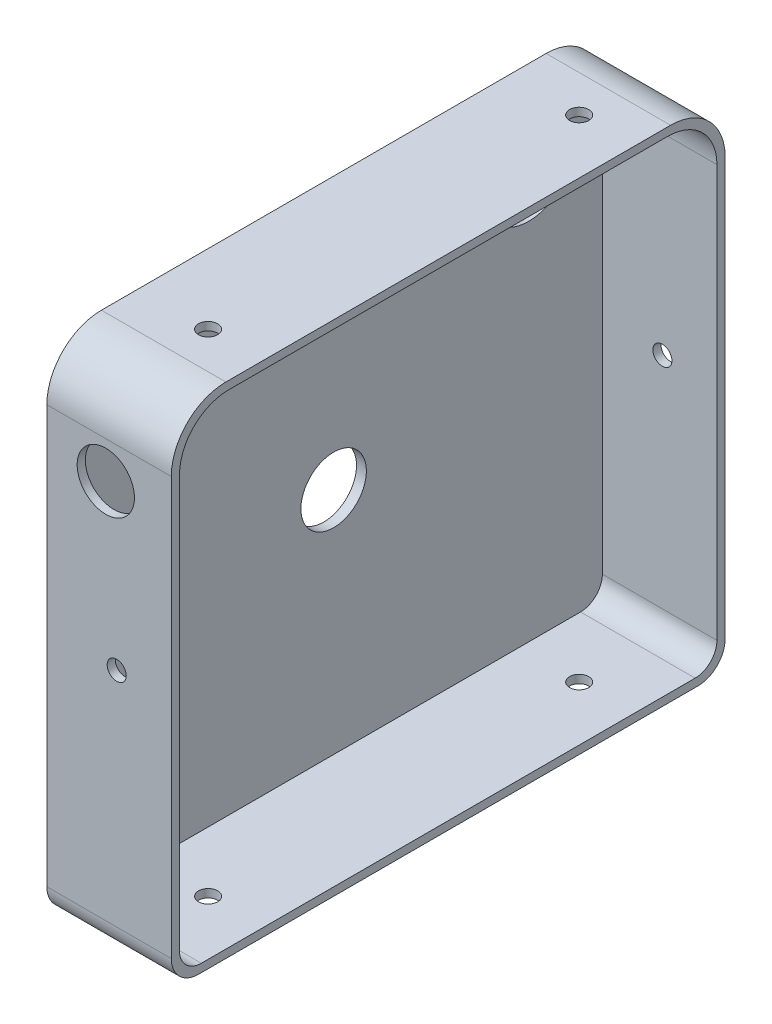
SolidWorks part; units mm, degrees
ref_plane "前视基准面" through (0, 0, 0) normal (0, 0, 1) x (1, 0, 0)
ref_plane "上视基准面" through (0, 0, 0) normal (0, 1, 0) x (1, 0, 0)
ref_plane "右视基准面" through (0, 0, 0) normal (1, 0, 0) x (0, 0, -1)
sketch "草图1" plane through (0, 0, 0) normal (1, 0, 0) x (0, 0, -1)
  line L0 (1.5, 1.5) -> (1.5, 90)
  line L1 (0, 0) -> (101.5, 0)
  line L2 (0, 0) -> (0, 91.5)
  line L3 (0, 91.5) -> (101.5, 91.5)
  line L4 (101.5, 0) -> (101.5, 91.5)
  line L5 (1.5, 90) -> (100, 90)
  line L6 (100, 1.5) -> (100, 90)
  line L7 (1.5, 1.5) -> (100, 1.5)
  dimension "D1" = 101.5
  dimension "D2" = 91.5
  dimension "D3" = 1.5
extrude "凸台-拉伸1" add sketch "草图1" along normal blind 21
sketch "草图2" plane through (0, 0, 0) normal (-1, 0, 0) x (0, 0, 1)
  line L0 (-50.75, 90) -> (-50.75, -4.3889) construction
  line L1 (-101.5, 91.5) -> (0, 91.5)
  line L2 (-101.5, 91.5) -> (-101.5, 0)
  line L3 (-101.5, 0) -> (0, 0)
  line L4 (0, 91.5) -> (0, 0)
  line L5 (-100, 90) -> (-1.5, 90) construction
  line L6 (-1.5, 1.5) -> (-100, 1.5) construction
  circle A0 centre (-86.5, 76.5) radius 8.25
  circle A1 centre (-50.75, 43.5) radius 6
  dimension "D1" = 12
  dimension "D2" = 16.5
  dimension "D5" = 42
  dimension "D3" = 15
  dimension "D4" = 15
extrude "凸台-拉伸2" add sketch "草图2" along normal blind 1.8
sketch "草图3" plane through (0, 0, 0) normal (0, 0, 1) x (1, 0, 0)
  line L0 (11, 95.0538) -> (11, -6.5657) construction
  line L3 (-1.8, 45.75) -> (35.7467, 45.75) construction
  line L4 (-1.8, 0) -> (-1.8, 91.5) construction
  line L5 (21, 91.5) -> (21, 0) construction
  circle A1 centre (11, 45.75) radius 1.75
  point P8 (12.2397, 46)
  point P11 (10, 46)
  dimension "D1" = 10
  dimension "D2" = 3.5
extrude "切除-拉伸1" cut sketch "草图3" against normal through all
sketch "草图4" plane through (0, 91.5, 0) normal (0, 1, 0) x (1, 0, 0)
  line L0 (11, 109.1455) -> (11, -1.1086) construction
  line L3 (21, 50.75) -> (-1.8, 50.75) construction
  line L4 (21, 101.5) -> (21, 0) construction
  line L5 (-1.8, 0) -> (-1.8, 101.5) construction
  circle A1 centre (11, 16.75) radius 1.75
  circle A2 centre (11, 84.75) radius 1.75
  point P6 (12.3214, 109.1455)
  point P16 (9.25, 8.3176)
  point P17 (0, 0)
  point P18 (9.25, -1.1086)
  point P19 (0, 0)
  point P20 (0, 0)
  dimension "D1" = 68
  dimension "D2" = 3.5
  dimension "D3" = 10
extrude "切除-拉伸2" cut sketch "草图4" against normal through all
fillet "圆角1" radius 9 2 edges at (10.5, 90, -1.5) (10.5, 90, -100)
fillet "圆角2" radius 10 2 edges at (9.6, 91.5, -101.5) (9.6, 91.5, 0)
fillet "圆角3" radius 4 2 edges at (10.5, 1.5, -1.5) (10.5, 1.5, -100)
fillet "圆角4" radius 5 2 edges at (9.6, 0, -101.5) (9.6, 0, 0)
sketch "草图5" plane through (-1.8, 0, 0) normal (-1, 0, 0) x (0, 0, 1)
  line L0 (-30.75, 43.5) -> (-20.75, 43.5)
  line L1 (-50.75, 43.5) -> (16.8741, 43.5) construction
  arc A0 (-20.75, 43.5) -> (-70.75, 43.5) centre (-45.75, 43.5) ccw
  arc A1 (-30.75, 43.5) -> (-70.75, 43.5) centre (-50.75, 43.5) ccw
  point P7 (-50.0123, 43.5)
  dimension "D1" = 25
  dimension "D2" = 20
extrude "切除-拉伸3" cut sketch "草图5" against normal blind 1
sketch "草图6" plane through (0, 0, 0) normal (0, 0, 1) x (1, 0, 0)
  line L0 (-1.8, 91.5) -> (21, 91.5) construction
  line L1 (-1.8, 5) -> (-1.8, 81.5) construction
  circle A0 centre (9, 74.75) radius 5.25
  dimension "D1" = 10.5
  dimension "D2" = 16.75
  dimension "D3" = 10.8
extrude "切除-拉伸4" cut sketch "草图6" against normal up to next
